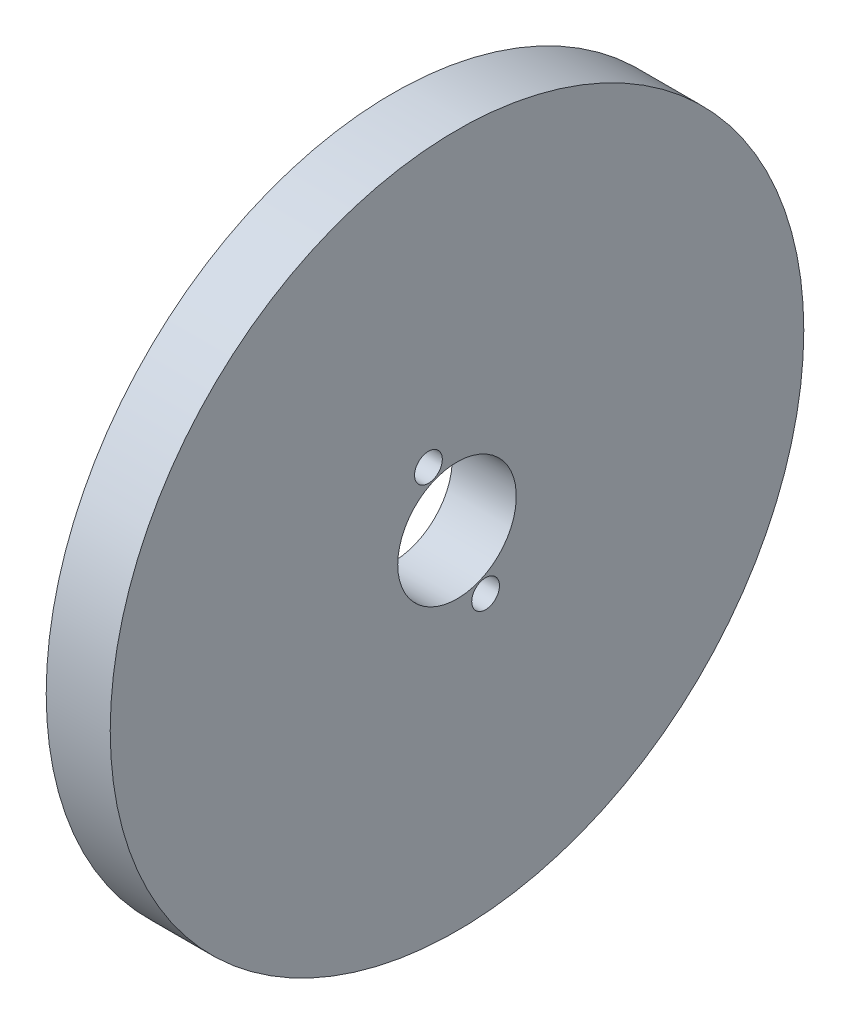
SolidWorks part; units mm, degrees
ref_plane "Front Plane" through (0, 0, 0) normal (0, 0, 1) x (1, 0, 0)
ref_plane "Top Plane" through (0, 0, 0) normal (0, 1, 0) x (1, 0, 0)
ref_plane "Right Plane" through (0, 0, 0) normal (1, 0, 0) x (0, 0, -1)
sketch "Axial profile (mm)" plane through (0, 0, 0) normal (0, 0, 1) x (1, 0, 0)
  line L0 (-110, 0) -> (75, 0) construction
  line L1 (13.7, 11.1125) -> (25.7, 11.1125)
  line L2 (25.7, 11.1125) -> (25.7, 65)
  line L3 (25.7, 65) -> (13.7, 65)
  line L4 (13.7, 65) -> (13.7, 11.1125)
revolve "Full revolution" add sketch "Axial profile (mm)" angle 360 about L0
sketch "Sketch2" plane through (0, 0, 0) normal (1, 0, 0) x (0, 0, -1)
  circle A0 centre (-5.3576, 12.9343) radius 2.6
  circle A1 centre (5.3576, -12.9343) radius 2.6
extrude "Axial holes" cut sketch "Sketch2" against normal through all and the other way through all
